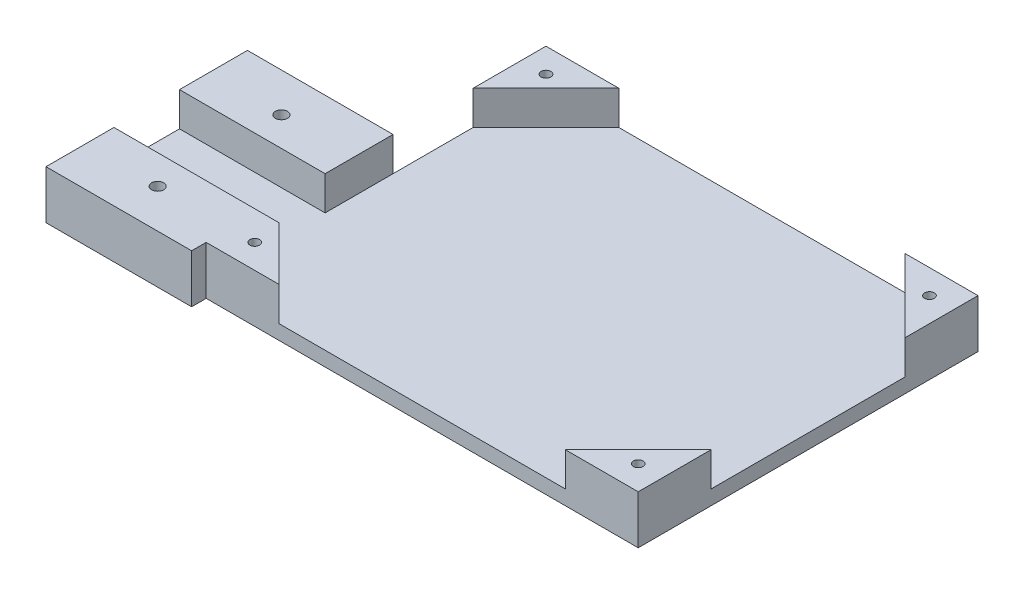
SolidWorks part; units mm, degrees
ref_plane "Front Plane" through (0, 0, 0) normal (0, 0, 1) x (1, 0, 0)
ref_plane "Top Plane" through (0, 0, 0) normal (0, 1, 0) x (1, 0, 0)
ref_plane "Right Plane" through (0, 0, 0) normal (1, 0, 0) x (0, 0, -1)
sketch "Sketch1" plane through (0, 0, 0) normal (0, 1, 0) x (1, 0, 0)
  line L1 (-44.5, -35) -> (44.5, -35)
  line L2 (-44.5, -35) -> (-44.5, 35)
  line L3 (-44.5, 35) -> (44.5, 35)
  line L4 (44.5, -35) -> (44.5, 35)
  line L5 (0, 35) -> (0, -35) construction
  line L6 (-44.5, 0) -> (44.5, 0) construction
  circle A0 centre (-39.5, 30) radius 1
  circle A1 centre (39.5, 30) radius 1
  circle A2 centre (39.5, -30) radius 1
  circle A3 centre (-39.5, -30) radius 1
  point P0 (0, 0)
  dimension "D3" = 2
  dimension "D1" = 89
  dimension "D2" = 70
  dimension "D4" = 5
  dimension "D5" = 5
extrude "Boss-Extrude1" add sketch "Sketch1" along normal blind 10
sketch "Sketch3" plane through (0, 10, 0) normal (0, 1, 0) x (1, 0, 0)
  line L0 (-44.5, -20) -> (-29.5, -35)
  line L1 (-44.5, 35) -> (-44.5, -35) construction
  line L2 (-44.5, -35) -> (44.5, -35) construction
  line L3 (-29.5, -35) -> (29.5, -35)
  line L4 (29.5, -35) -> (44.5, -20)
  line L5 (44.5, -35) -> (44.5, 35) construction
  line L6 (44.5, -20) -> (44.5, 20)
  line L7 (44.5, 20) -> (29.5, 35)
  line L8 (44.5, 35) -> (-44.5, 35) construction
  line L9 (29.5, 35) -> (-29.5, 35)
  line L10 (-29.5, 35) -> (-44.5, 20)
  line L11 (-44.5, 20) -> (-44.5, -20)
  line L12 (44.5, 20) -> (44.5, 27.0203) construction
  line L13 (-44.5, 20) -> (-44.5, 25.3065) construction
  dimension "D1" = 45
  dimension "D2" = 15
  dimension "D3" = 45
extrude "Cut-Extrude2" cut sketch "Sketch3" against normal blind 7
sketch "Sketch6" plane through (0, 0, 0) normal (0, -1, 0) x (1, 0, 0)
  line L0 (-44.5, -20) -> (-44.5, 20) construction
  line L1 (-44.5, -3.5) -> (-74.5, -3.5)
  line L2 (-44.5, -3.5) -> (-44.5, 38)
  line L3 (-44.5, 38) -> (-74.5, 38)
  line L4 (-74.5, -3.5) -> (-74.5, 38)
  circle A0 centre (-59.5, 30) radius 1.25
  circle A1 centre (-59.5, 4.5) radius 1.25
  point P10 (0, 0)
  point P12 (-39.5, 30)
  dimension "D2" = 2.5
  dimension "D1" = 25.5
  dimension "D3" = 15
  dimension "D4" = 30
  dimension "D5" = 8
  dimension "D6" = 8
extrude "Boss-Extrude2" add sketch "Sketch6" against normal blind 10
sketch "Sketch7" plane through (0, 10, 0) normal (0, 1, 0) x (1, 0, 0)
  line L0 (-74.5, -38) -> (-74.5, 3.5) construction
  line L1 (-74.5, -10.5) -> (-40.5, -10.5)
  line L2 (-74.5, -10.5) -> (-74.5, -24)
  line L3 (-74.5, -24) -> (-40.5, -24)
  line L4 (-40.5, -10.5) -> (-40.5, -24)
  line L5 (-44.5, -20) -> (-29.5, -35) construction
  circle A0 centre (-59.5, -4.5) radius 1.25 construction
  circle A1 centre (-59.5, -30) radius 1.25 construction
  dimension "D1" = 6
  dimension "D2" = 6
extrude "Cut-Extrude3" cut sketch "Sketch7" against normal blind 7
